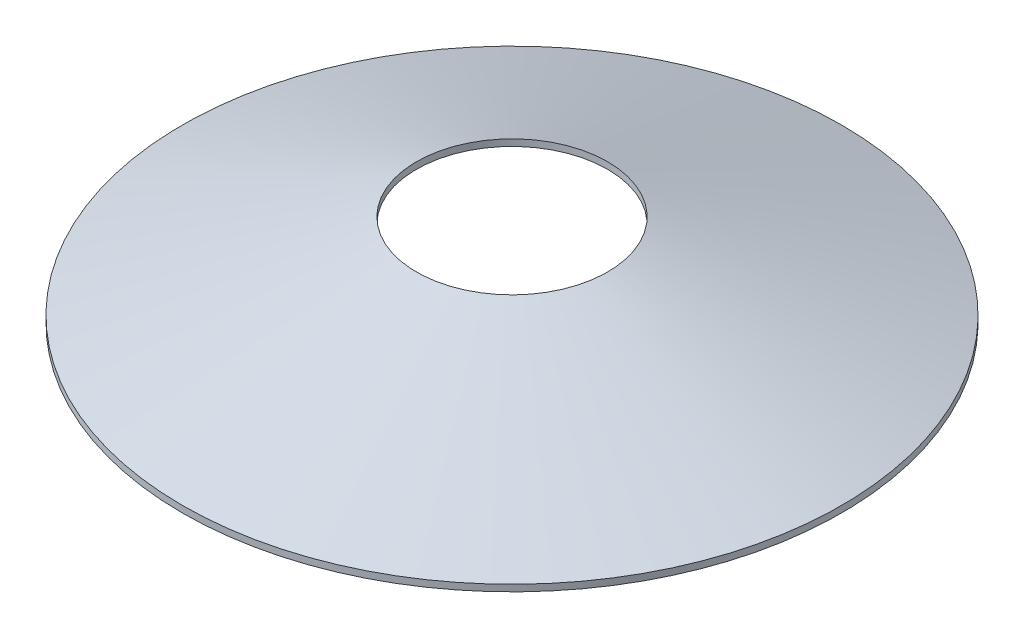
SolidWorks part; units mm, degrees
ref_plane "Piano frontale" through (0, 0, 0) normal (0, 0, 1) x (1, 0, 0)
ref_plane "Piano superiore" through (0, 0, 0) normal (0, 1, 0) x (1, 0, 0)
ref_plane "Piano destro" through (0, 0, 0) normal (1, 0, 0) x (0, 0, -1)
sketch "Schizzo1" plane through (0, 0, 0) normal (0, 0, 1) x (1, 0, 0)
  line L0 (0, 0) -> (-17.5757, 0)
  line L1 (-17.5757, 0) -> (-100, -30)
  line L2 (-100, -30) -> (-100, -32)
  line L3 (-100, -32) -> (-17.5757, -2)
  line L4 (-17.5757, -2) -> (0, -2)
  line L5 (0, -2) -> (0, 0)
  dimension "D1" = 2
  dimension "D2" = 100
  dimension "D3" = 20
  dimension "D4" = 2
  dimension "D5" = 32
revolve "Rivoluzione1" add sketch "Schizzo1" angle 360 about L5
sketch "Schizzo4" plane through (0, 0, 0) normal (0, 1, 0) x (1, 0, 0)
  circle A0 centre (0, 0) radius 29
  dimension "D1" = 58
extrude "Taglio-Estrusione1" cut sketch "Schizzo4" against normal through all
